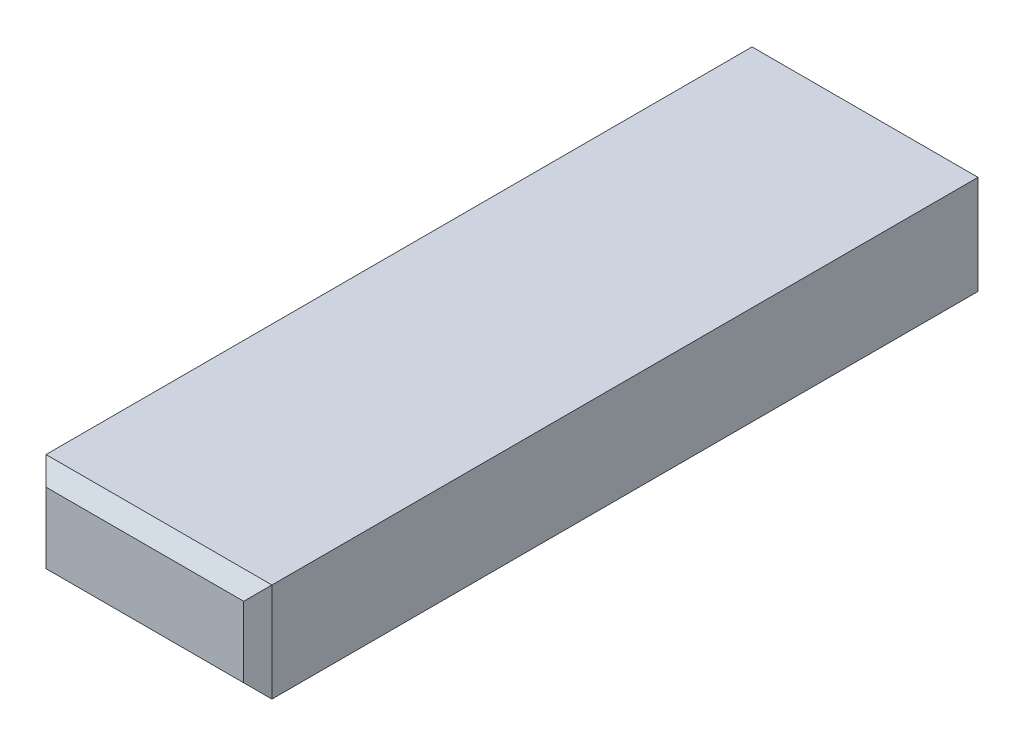
SolidWorks part; units mm, degrees
ref_plane "Front Plane" through (0, 0, 0) normal (0, 0, 1) x (1, 0, 0)
ref_plane "Top Plane" through (0, 0, 0) normal (0, 1, 0) x (1, 0, 0)
ref_plane "Right Plane" through (0, 0, 0) normal (1, 0, 0) x (0, 0, -1)
sketch "Sketch1" plane through (0, 0, 0) normal (0, 0, 1) x (1, 0, 0)
  line L1 (-4, 1.75) -> (4, 1.75)
  line L2 (-4, 1.75) -> (-4, -1.75)
  line L3 (-4, -1.75) -> (4, -1.75)
  line L4 (4, 1.75) -> (4, -1.75)
  line L5 (0, -1.75) -> (0, 1.75) construction
  line L6 (-4, 0) -> (4, 0) construction
  point P0 (0, 0)
  dimension "D1" = 3.5
  dimension "D2" = 8
extrude "Boss-Extrude1" add sketch "Sketch1" along normal mid plane 10
sketch "Sketch2" plane through (0, 0, -5) normal (0, 0, -1) x (-1, 0, 0)
  line L1 (-4, 1.75) -> (4, 1.75)
  line L2 (-4, 1.75) -> (-4, -1.75)
  line L3 (-4, -1.75) -> (4, -1.75)
  line L4 (4, 1.75) -> (4, -1.75)
  line L5 (0, -1.75) -> (0, 1.75) construction
  line L6 (-4, 0) -> (4, 0) construction
  point P0 (0, 0)
  dimension "D1" = 3.5
  dimension "D2" = 8
extrude "Boss-Extrude2" add sketch "Sketch2" along normal blind 8
mirror "Mirror1" about plane through (0, 0, 0) normal (0, 0, 1) of "Boss-Extrude2"
chamfer "Chamfer1" distance 0.5 angle 45 12 edges at (-4, 1.75, 0) (-4, 0, 13) (4, 0, 13) (0, -1.75, 13) (0, 1.75, 13) (-4, 0, -13) (0, 1.75, -13) (4, 1.75, 0) (4, 0, -13) (-4, -1.75, 0) (4, -1.75, 0) (0, -1.75, -13)
